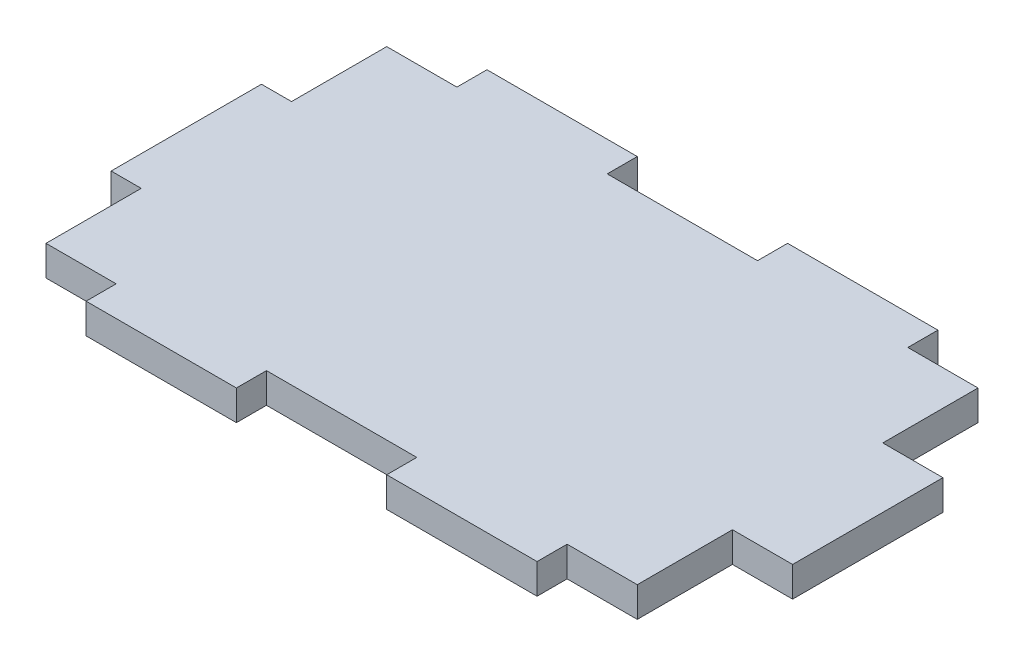
SolidWorks part; units mm, degrees
ref_plane "Alzado" through (0, 0, 0) normal (0, 0, 1) x (1, 0, 0)
ref_plane "Planta" through (0, 0, 0) normal (0, 1, 0) x (1, 0, 0)
ref_plane "Vista lateral" through (0, 0, 0) normal (1, 0, 0) x (0, 0, -1)
sketch "Croquis1" plane through (0, 0, 0) normal (0, 1, 0) x (1, 0, 0)
  line L0 (10, 0) -> (25, 0)
  line L1 (0, 12.5) -> (0, 27.5)
  line L2 (0, 20) -> (0, 27.5)
  line L3 (0, 27.5) -> (3, 27.5)
  line L4 (3, 27.5) -> (3, 37)
  line L5 (40, 0) -> (55, 0)
  line L6 (3, 12.5) -> (3, 3)
  line L7 (0, 12.5) -> (3, 12.5)
  line L8 (10, 40) -> (25, 40)
  line L9 (68, 27.5) -> (68, 12.5)
  line L10 (10, 0) -> (10, 3)
  line L11 (40, 37) -> (25, 37)
  line L12 (25, 37) -> (25, 40)
  line L13 (25, 40) -> (10, 40)
  line L14 (10, 40) -> (10, 37)
  line L15 (10, 37) -> (3, 37)
  line L16 (25, 3) -> (25, 0)
  line L17 (40, 3) -> (25, 3)
  line L18 (40, 3) -> (40, 0)
  line L19 (55, 37) -> (62, 37)
  line L20 (55, 40) -> (55, 37)
  line L21 (40, 37) -> (40, 40)
  line L22 (68, 12.5) -> (62, 12.5)
  line L23 (62, 12.5) -> (62, 3)
  line L24 (40, 40) -> (55, 40)
  line L25 (62, 27.5) -> (62, 37)
  line L26 (68, 27.5) -> (62, 27.5)
  line L27 (10, 3) -> (3, 3)
  line L28 (55, 0) -> (55, 3)
  line L29 (55, 3) -> (62, 3)
  point P24 (32.5, 3)
  dimension "D1" = 6
  dimension "D3" = 3
  dimension "D6" = 15
extrude "Saliente-Extruir1" add sketch "Croquis1" along normal blind 3 contours L28 L29 L23 L22 L9 L26 L25 L19 L20 L24 L21 L11 L12 L8 L14 L15 L4 L3 L1 L7 L6 L27 L10 L0 L16 L17 L18 L5
